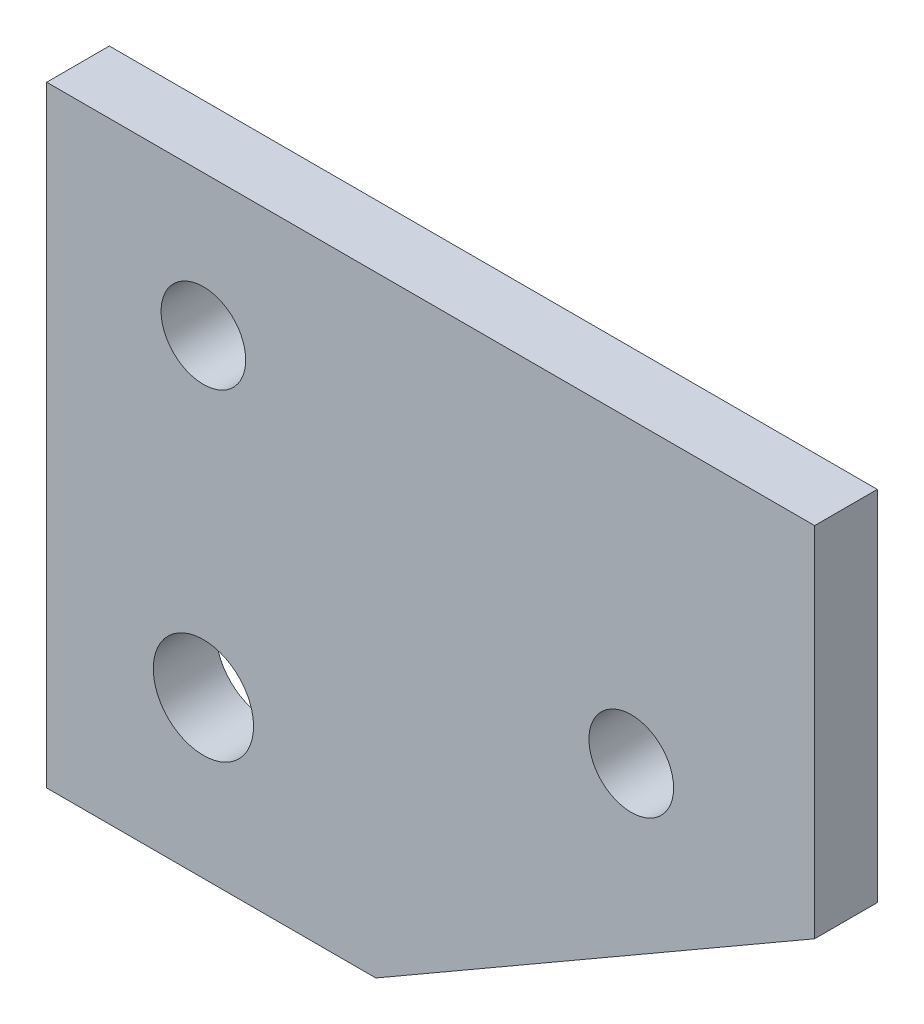
SolidWorks part; units mm, degrees
ref_plane "前视基准面" through (0, 0, 0) normal (0, 0, 1) x (1, 0, 0)
ref_plane "上视基准面" through (0, 0, 0) normal (0, 1, 0) x (1, 0, 0)
ref_plane "右视基准面" through (0, 0, 0) normal (1, 0, 0) x (0, 0, -1)
sketch "草图1" plane through (0, 0, 0) normal (0, 0, 1) x (1, 0, 0)
  line L1 (-56.4288, 21.1141) -> (-7.4288, 21.1141)
  line L2 (-56.4288, 21.1141) -> (-56.4288, -17.8859)
  line L3 (-56.4288, -17.8859) -> (-7.4288, -17.8859)
  line L4 (-7.4288, 21.1141) -> (-7.4288, -17.8859)
  dimension "D1" = 49
  dimension "D2" = 39
extrude "凸台-拉伸1" add sketch "草图1" along normal blind 4
sketch "草图2" plane through (0, 0, 0) normal (0, 0, 1) x (1, 0, 0)
  line L0 (-7.4288, -17.8859) -> (-35.4288, -17.8859)
  line L1 (-56.4288, -17.8859) -> (-7.4288, -17.8859) construction
  line L2 (-35.4288, -17.8859) -> (5.926, 5.9903)
  line L3 (5.926, 5.9903) -> (-7.4288, -17.8859)
  dimension "D1" = 28
  dimension "D2" = 30
extrude "切除-拉伸1" cut sketch "草图2" along normal blind 13
sketch "草图4" plane through (0, 0, 0) normal (0, 0, 1) x (1, 0, 0)
  circle A0 centre (-19.1288, 2.1141) radius 2.7
  dimension "D3" = 5.4
extrude "切除-拉伸2" cut sketch "草图4" along normal blind 17
sketch "草图5" plane through (0, 0, 0) normal (0, 0, 1) x (1, 0, 0)
  circle A0 centre (-46.4288, 12.1141) radius 2.7
  circle A1 centre (-46.4288, -7.8859) radius 3.2
  dimension "D4" = 5.4
  dimension "D5" = 6.4
extrude "切除-拉伸3" cut sketch "草图5" along normal blind 17
